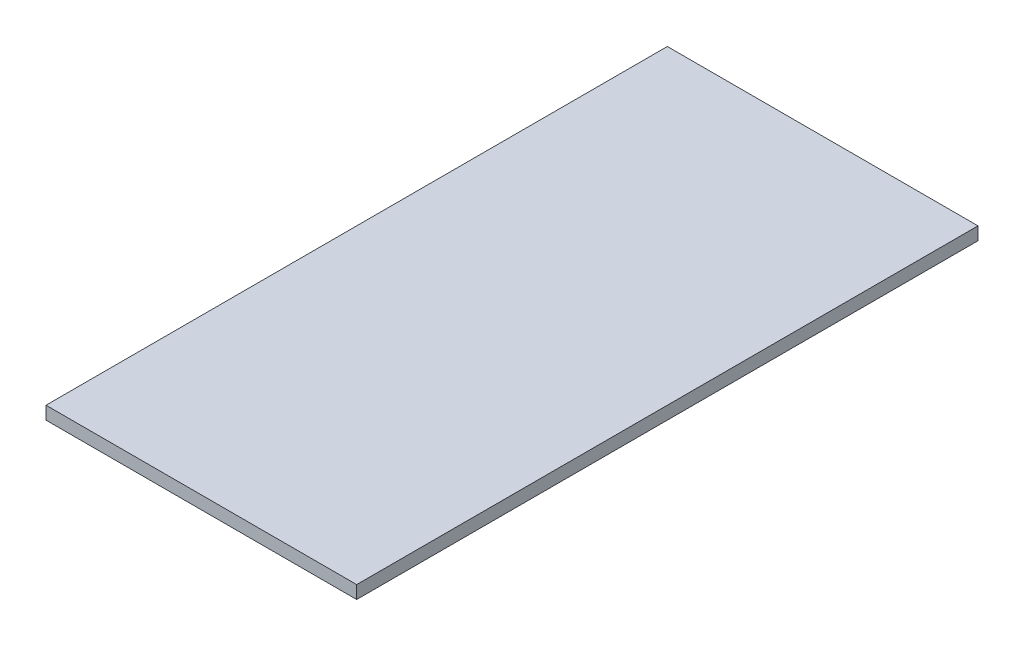
SolidWorks part; units mm, degrees
material "6061-T6 (SS)"
ref_plane "Front Plane" through (0, 0, 0) normal (0, 0, 1) x (1, 0, 0)
ref_plane "Top Plane" through (0, 0, 0) normal (0, 1, 0) x (1, 0, 0)
ref_plane "Right Plane" through (0, 0, 0) normal (1, 0, 0) x (0, 0, -1)
sketch "Sketch1" plane through (0, 0, 0) normal (0, 1, 0) x (1, 0, 0)
  line L1 (-38.1, -76.2) -> (38.1, -76.2)
  line L2 (-38.1, -76.2) -> (-38.1, 76.2)
  line L3 (-38.1, 76.2) -> (38.1, 76.2)
  line L4 (38.1, -76.2) -> (38.1, 76.2)
  line L5 (-38.1, -76.2) -> (38.1, 76.2) construction
  line L6 (-38.1, 76.2) -> (38.1, -76.2) construction
  point P0 (0, 0)
  dimension "D1" = 76.2
  dimension "D2" = 152.4
extrude "Boss-Extrude1" add sketch "Sketch1" along normal blind 3.175
